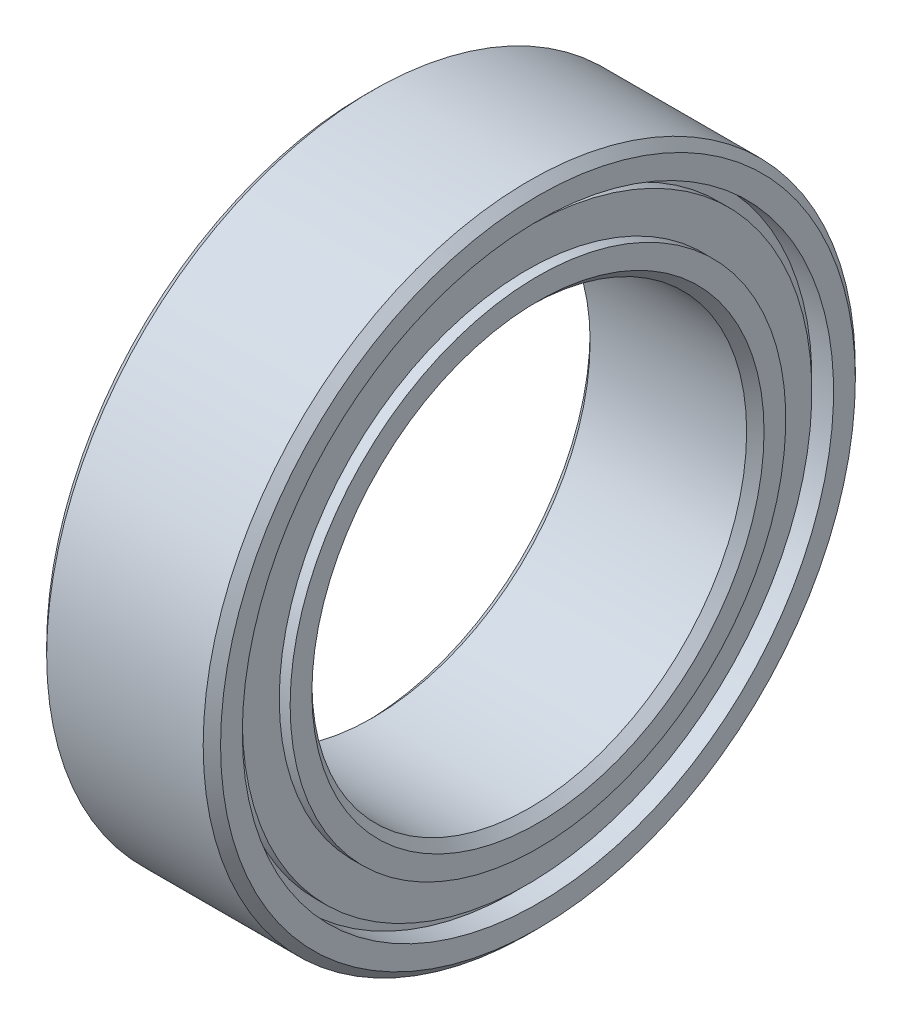
SolidWorks part; units mm, degrees
ref_plane "前视基准面" through (0, 0, 0) normal (0, 0, 1) x (1, 0, 0)
ref_plane "上视基准面" through (0, 0, 0) normal (0, 1, 0) x (1, 0, 0)
ref_plane "右视基准面" through (0, 0, 0) normal (1, 0, 0) x (0, 0, -1)
other "Configuration Table"
sketch "草图1" plane through (0, 0, 0) normal (0, 0, 1) x (1, 0, 0)
  line L0 (-3.901, 0) -> (3.7973, 0) construction
  line L1 (0, 7.17) -> (0, -5.7744) construction
  line L2 (-2, 5) -> (2, 5)
  line L3 (2, 5) -> (2, 5.7)
  line L4 (2, 5.7) -> (1.75, 5.7)
  line L5 (1.75, 5.7) -> (1.75, 6.55)
  line L6 (1.75, 6.55) -> (1.5, 6.55)
  line L7 (1.5, 6.55) -> (1.5, 6.8)
  line L8 (1.5, 6.8) -> (2, 6.8)
  line L9 (2, 6.8) -> (2, 7.5)
  line L10 (2, 7.5) -> (-2, 7.5)
  line L11 (-2, 6.8) -> (-2, 7.5)
  line L12 (-1.5, 6.8) -> (-2, 6.8)
  line L13 (-1.5, 6.55) -> (-1.5, 6.8)
  line L14 (-1.75, 6.55) -> (-1.5, 6.55)
  line L15 (-1.75, 5.7) -> (-1.75, 6.55)
  line L16 (-2, 5.7) -> (-1.75, 5.7)
  line L17 (-2, 5) -> (-2, 5.7)
  point P6 (-2, 5.35)
  point P16 (0, 7.5)
  point P23 (0, 5)
  dimension "D1" = 5
  dimension "D2" = 0.7
  dimension "D3" = 7.5
  dimension "D4" = 0.7
  dimension "D5" = 0.25
  dimension "D6" = 4
  dimension "D7" = 0.25
  dimension "D8" = 0.5
revolve "旋转1" add sketch "草图1" angle 360 about L0
chamfer "倒角1" distance 0.2 angle 45 4 edges at (2, 0, 7.5) (-2, 0, 7.5) (-2, 0, 5) (2, 0, 5)
